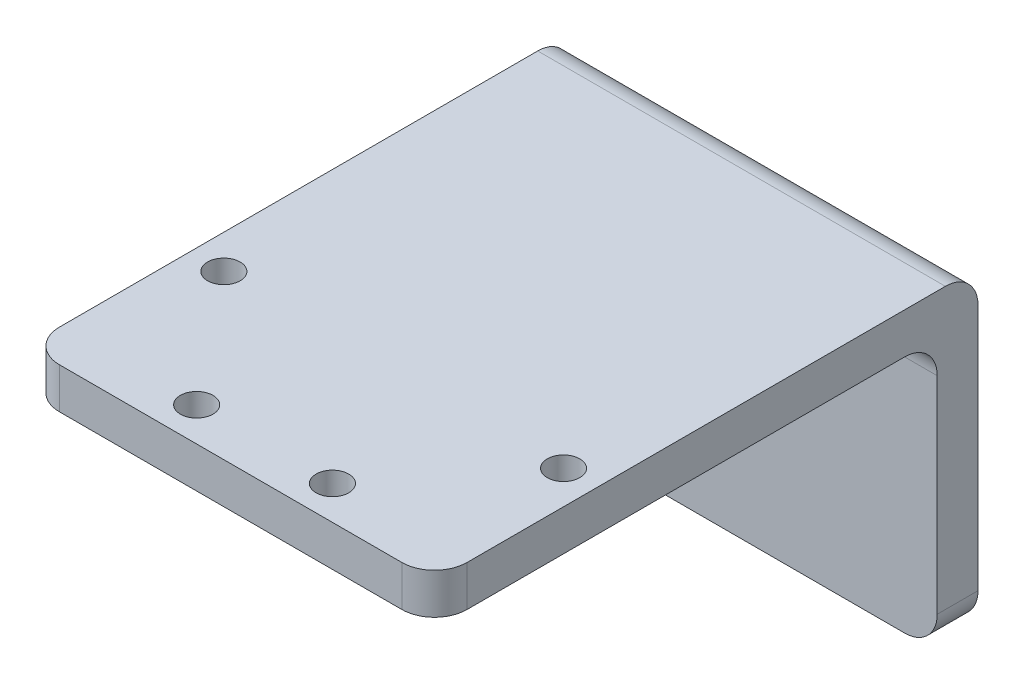
SolidWorks part; units mm, degrees
ref_plane "Plano frontal" through (0, 0, 0) normal (0, 0, 1) x (1, 0, 0)
ref_plane "Plano superior" through (0, 0, 0) normal (0, 1, 0) x (1, 0, 0)
ref_plane "Plano direito" through (0, 0, 0) normal (1, 0, 0) x (0, 0, -1)
sketch "Esboço1" plane through (0, 0, 0) normal (0, 1, 0) x (1, 0, 0)
  line L0 (0, 0) -> (0, 20) construction
  line L1 (-15, 20) -> (15, 20)
  line L2 (0, 0) -> (15, 0) construction
  line L3 (15, -20) -> (15, 20)
  line L4 (-15, 20) -> (-15, -20)
  line L5 (-15, -20) -> (15, -20)
  point P5 (0, 20)
  point P10 (15, 0)
  dimension "D1" = 30
  dimension "D2" = 40
extrude "Ressalto-extrusão1" add sketch "Esboço1" along normal blind 3
sketch "Esboço3" plane through (0, 0, 0) normal (0, -1, 0) x (1, 0, 0)
  line L0 (-15, -20) -> (-15, 20) construction
  line L1 (-15, 20) -> (15, 20) construction
  line L3 (0, 20) -> (0.0283, 5) construction
  line L4 (-15.9979, 5) -> (16.0545, 5) construction
  line L5 (54.6527, 5) -> (-54.4441, 5) construction
  circle A0 centre (-5, 17.5) radius 1.2
  circle A2 centre (-12.5, 8) radius 1.2
  circle A4 centre (12.5451, 8.0472) radius 1.2
  circle A5 centre (5.0094, 17.5189) radius 1.2
  dimension "D1" = 2.4
  dimension "D7" = 2.4
  dimension "D2" = 10
  dimension "D3" = 2.5
  dimension "D9" = 2.5
  dimension "D11" = 3
extrude "Corte-extrusão2" cut sketch "Esboço3" against normal through all
sketch "Esboço4" plane through (0, 0, 0) normal (0, -1, 0) x (1, 0, 0)
  line L0 (-15, -17) -> (15, -17)
  line L4 (-15, 20) -> (-15, -20)
  line L5 (-15, -20) -> (15, -20)
  line L6 (15, -20) -> (15, 20)
  line L7 (15, 20) -> (-15, 20)
  line L8 (-15, 20) -> (-15, -20)
  line L9 (-15, -20) -> (15, -20)
  line L10 (15, -20) -> (15, 20)
  line L11 (15, 20) -> (-15, 20)
  dimension "D2" = 3
  dimension "D1" = 0
extrude "Ressalto-extrusão2" add sketch "Esboço4" along normal blind 20
fillet "Filete5" radius 2.4 1 edges at (0, 0, -17)
fillet "Filete6" radius 2.4 1 edges at (0, 3, -20)
fillet "Filete7" radius 2.4 2 edges at (15, 1.5, 20) (-15, 1.5, 20)
fillet "Filete8" radius 2.4 2 edges at (-15, -20, -18.5) (15, -20, -18.5)
